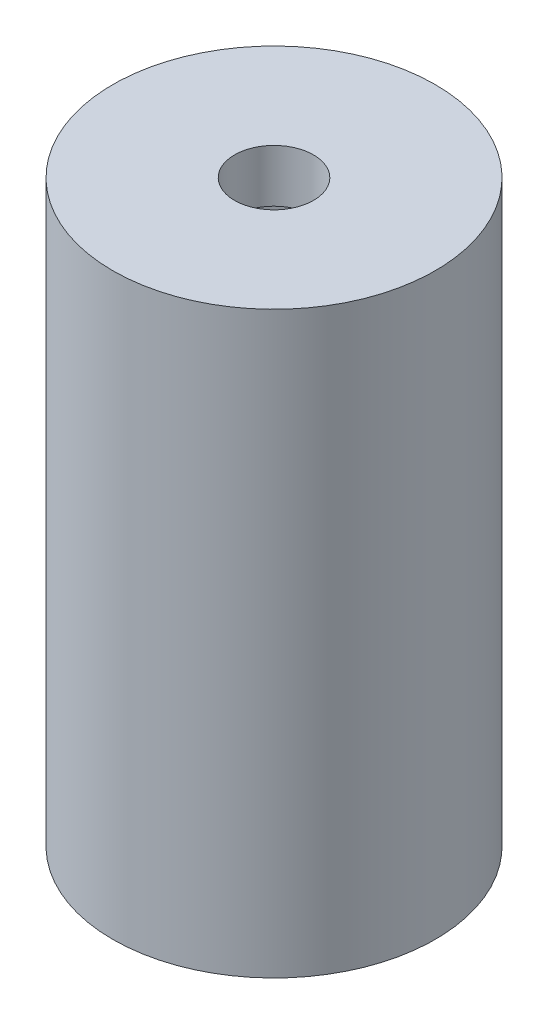
SolidWorks part; units mm, degrees
ref_plane "Alzado" through (0, 0, 0) normal (0, 0, 1) x (1, 0, 0)
ref_plane "Planta" through (0, 0, 0) normal (0, 1, 0) x (1, 0, 0)
ref_plane "Vista lateral" through (0, 0, 0) normal (1, 0, 0) x (0, 0, -1)
sketch "Croquis1" plane through (0, 0, 0) normal (0, 1, 0) x (1, 0, 0)
  line L2 (-3, 11.877) -> (-3, 8.4853)
  line L3 (3, 11.877) -> (3, 8.4853)
  arc A0 (-3, 8.4853) -> (3, 8.4853) centre (0, 0) ccw
  arc A1 (-3, 11.877) -> (3, 11.877) centre (0, 0) ccw
  point P9 (0, 11)
  dimension "D1" = 18
  dimension "D2" = 24.5
extrude "Saliente-Extruir1" add sketch "Croquis1" along normal blind 40
sketch "Croquis2" plane through (0, 40, 0) normal (0, 1, 0) x (1, 0, 0)
  circle A0 centre (0, 0) radius 12.25
extrude "Saliente-Extruir2" add sketch "Croquis2" along normal blind 4
sketch "Croquis3" plane through (0, 44, 0) normal (0, 1, 0) x (1, 0, 0)
  circle A0 centre (0, 0) radius 3
  dimension "D1" = 6
extrude "Cortar-Extruir1" cut sketch "Croquis3" against normal blind 4
